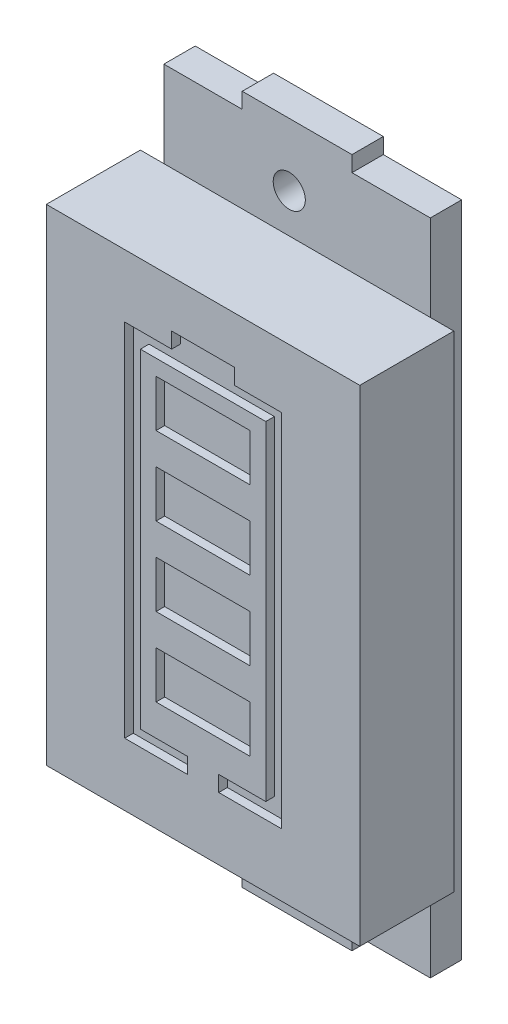
SolidWorks part; units mm, degrees
ref_plane "Front Plane" through (0, 0, 0) normal (0, 0, 1) x (1, 0, 0)
ref_plane "Top Plane" through (0, 0, 0) normal (0, 1, 0) x (1, 0, 0)
ref_plane "Right Plane" through (0, 0, 0) normal (1, 0, 0) x (0, 0, -1)
sketch "Sketch1" plane through (0, 0, 0) normal (0, 0, 1) x (1, 0, 0)
  line L0 (-3.5, 22) -> (3.5, 22)
  line L1 (-8.5, 21) -> (-3.5, 21)
  line L2 (-8.5, 21) -> (-8.5, -21)
  line L3 (-8.5, -21) -> (-3.5, -21)
  line L4 (8.5, 21) -> (8.5, -21)
  line L6 (-3.5, -22) -> (3.5, -22)
  line L8 (-3.5, 22) -> (-3.5, 21)
  line L9 (3.5, 22) -> (3.5, 21)
  line L10 (-9.5, 22) -> (9.5, 22) construction
  line L11 (-9.5, 22) -> (-9.5, -22) construction
  line L12 (-3.5, -21) -> (-3.5, -22)
  line L13 (3.5, -21) -> (3.5, -22)
  line L14 (3.5, 21) -> (8.5, 21)
  line L15 (-9.5, -22) -> (9.5, -22) construction
  line L16 (9.5, 22) -> (9.5, -22) construction
  line L17 (-8.5, 21) -> (8.5, 21) construction
  line L18 (3.5, -21) -> (8.5, -21)
  line L19 (-8.5, -21) -> (8.5, -21) construction
  point P6 (-8.5, 0)
  dimension "D1" = 17
  dimension "D2" = 44
  dimension "D3" = 1
  dimension "D4" = 42
extrude "Boss-Extrude1" add sketch "Sketch1" along normal blind 2 contours L2 L3 L12 L6 L13 L18 L4 L14 L9 L0 L8 L1
sketch "Sketch2" plane through (0, 0, 2) normal (0, 0, 1) x (1, 0, 0)
  line L1 (-10, 15.5) -> (10, 15.5)
  line L2 (-10, 15.5) -> (-10, -15.5)
  line L3 (-10, -15.5) -> (10, -15.5)
  line L4 (10, 15.5) -> (10, -15.5)
  point P4 (0, -15.5)
  point P6 (10, 0)
  dimension "D1" = 20
  dimension "D2" = 31
extrude "Boss-Extrude2" add sketch "Sketch2" along normal blind 6 separate body
sketch "Sketch3" plane through (0, 0, 8) normal (0, 0, 1) x (1, 0, 0)
  line L0 (-1, -11.5) -> (-5, -11.5)
  line L1 (4, -10.5) -> (1, -10.5)
  line L2 (4, -10.5) -> (4, 10.5)
  line L3 (4, 10.5) -> (-4, 10.5)
  line L4 (-4, -10.5) -> (-4, 10.5)
  line L5 (4, -10.5) -> (-4, 10.5) construction
  line L6 (4, 10.5) -> (-4, -10.5) construction
  line L7 (-5, -11.5) -> (-5, 11.5)
  line L8 (5, 11.5) -> (2, 11.5)
  line L9 (5, -11.5) -> (5, 11.5)
  line L10 (-1, -10.5) -> (-4, -10.5)
  line L11 (5, -11.5) -> (1, -11.5)
  line L12 (2, 12.5) -> (-2, 12.5)
  line L13 (-1, -10.5) -> (-1, -11.5)
  line L14 (1, -10.5) -> (1, -11.5)
  line L15 (-2, 11.5) -> (-2, 12.5)
  line L16 (-2, 11.5) -> (-5, 11.5)
  line L17 (5, 11.5) -> (-5, 11.5) construction
  line L18 (-3, -0.5) -> (-3, -3.5)
  line L19 (-3, -5.5) -> (3, -5.5)
  line L20 (5, 12.5) -> (-5, 12.5) construction
  line L21 (2, 11.5) -> (2, 12.5)
  line L22 (-3, -5.5) -> (-3, -8.5)
  line L23 (-3, -8.5) -> (3, -8.5)
  line L24 (3, -5.5) -> (3, -8.5)
  line L25 (-3, -0.5) -> (3, -0.5)
  line L26 (3, -0.5) -> (3, -3.5)
  line L27 (-3, -3.5) -> (3, -3.5)
  line L28 (-3, 4.5) -> (-3, 1.5)
  line L29 (-3, 4.5) -> (3, 4.5)
  line L30 (3, 4.5) -> (3, 1.5)
  line L31 (-3, 1.5) -> (3, 1.5)
  line L32 (-3, 9.5) -> (-3, 6.5)
  line L33 (-3, 9.5) -> (3, 9.5)
  line L34 (3, 9.5) -> (3, 6.5)
  line L35 (-3, 6.5) -> (3, 6.5)
  point P0 (0, 0)
  point P24 (0, -5.5)
  dimension "D1" = 8
  dimension "D2" = 21
  dimension "D3" = 2
  dimension "D4" = 6
  dimension "D5" = 3
  dimension "D6" = 4
extrude "Cut-Extrude1" cut sketch "Sketch3" against normal blind 0.55
sketch "Sketch5" plane through (0, 0, 0) normal (0, 0, -1) x (-1, 0, 0)
  line L0 (-8.5, 21) -> (-8.5, -21) construction
  line L1 (-3.5, 21) -> (-8.5, 21) construction
  circle A0 centre (0.5, 18) radius 1
  circle A1 centre (0.5, -18) radius 1
  dimension "D4" = 2
  dimension "D1" = 9
  dimension "D2" = 3
  dimension "D3" = 2
hole_wizard "Tap Drill for M2.5x0.45 Tap1" positions "3DSketch2" profile "Sketch6" hole size "M2.5x0.45" standard "ANSI Metric" end condition through all
sketch3d "3DSketch2"
  point P0 (-0.5, 18, 0)
  point P3 (-0.5, -18, 0)
sketch "Sketch6" plane through (-0.5, 18, 0) normal (1, 0, 0) x (0, 1, 0)
  line L0 (0, 0) -> (0, 8)
  line L1 (0, 8) -> (1.025, 8)
  line L2 (1.025, 8) -> (1.025, 0)
  line L5 (1.025, 0) -> (0, 0)
  line L11 (0, -6.35) -> (0, 107.95) construction
  dimension "Thru Hole Dia." = 2.05
  dimension "Thru Hole Depth" = 8
